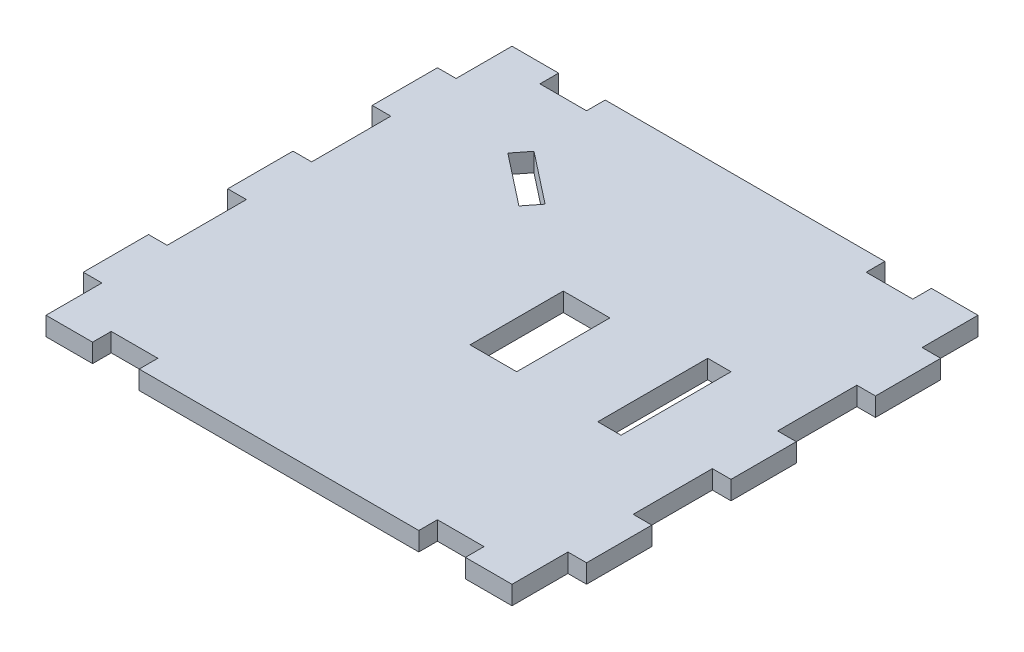
SolidWorks part; units mm, degrees
ref_plane "Front Plane" through (0, 0, 0) normal (0, 0, 1) x (1, 0, 0)
ref_plane "Top Plane" through (0, 0, 0) normal (0, 1, 0) x (1, 0, 0)
ref_plane "Right Plane" through (0, 0, 0) normal (1, 0, 0) x (0, 0, -1)
sketch "Sketch1" plane through (0, 0, 0) normal (0, 1, 0) x (1, 0, 0)
  line L1 (-25, 25) -> (25, 25)
  line L2 (-25, 25) -> (-25, -25)
  line L3 (-25, -25) -> (25, -25)
  line L4 (25, 25) -> (25, -25)
  line L5 (-25, 25) -> (25, -25) construction
  line L6 (-25, -25) -> (25, 25) construction
  line L7 (25, -19) -> (27, -19)
  line L8 (25, -19) -> (25, -12)
  line L9 (25, -12) -> (27, -12)
  line L10 (27, -19) -> (27, -12)
  line L11 (25, -3.5) -> (27, -3.5)
  line L12 (25, -3.5) -> (25, 3.5)
  line L13 (25, 3.5) -> (27, 3.5)
  line L14 (27, -3.5) -> (27, 3.5)
  line L15 (25, 12) -> (27, 12)
  line L16 (25, 12) -> (25, 19)
  line L17 (25, 19) -> (27, 19)
  line L18 (27, 12) -> (27, 19)
  line L19 (14.5, 6.5) -> (17, 6.5)
  line L20 (14.5, 6.5) -> (14.5, -5.3)
  line L21 (14.5, -5.3) -> (17, -5.3)
  line L22 (17, 6.5) -> (17, -5.3)
  line L23 (-25, 19) -> (-27, 19)
  line L24 (-25, 19) -> (-25, 12)
  line L25 (-25, 12) -> (-27, 12)
  line L26 (-27, 19) -> (-27, 12)
  line L27 (-25, 3.5) -> (-27, 3.5)
  line L28 (-25, 3.5) -> (-25, -3.5)
  line L29 (-25, -3.5) -> (-27, -3.5)
  line L30 (-27, 3.5) -> (-27, -3.5)
  line L31 (-25, -12) -> (-27, -12)
  line L32 (-25, -12) -> (-25, -19)
  line L33 (-25, -19) -> (-27, -19)
  line L34 (-27, -12) -> (-27, -19)
  point P0 (0, 0)
  dimension "D1" = 50
  dimension "D2" = 50
  dimension "D3" = 2
  dimension "D4" = 2
  dimension "D5" = 2
  dimension "D6" = 7
  dimension "D7" = 7
  dimension "D8" = 7
  dimension "D9" = 6
  dimension "D10" = 8.5
  dimension "D11" = 8.5
  dimension "D12" = 6
  dimension "D13" = 2.5
  dimension "D14" = 11.8
  dimension "D15" = 18.5
  dimension "D16" = 19.7
  dimension "D17" = 8
  dimension "D18" = 7
  dimension "D19" = 7
  dimension "D20" = 7
  dimension "D21" = 2
  dimension "D22" = 2
  dimension "D23" = 2
  dimension "D24" = 8.5
  dimension "D25" = 8.5
  dimension "D26" = 6
  dimension "D27" = 6
extrude "Boss-Extrude1" add sketch "Sketch1" along normal blind 2 contours L4 L1 L2 L3 L19 L22 L21 L20 | L11 L14 L13 L4 | L15 L18 L17 L4 | L7 L10 L9 L4 | L27 L30 L29 L2 | L31 L34 L33 L2 | L26 L25 L24 L23
sketch "Sketch3" plane through (0, 2, 0) normal (0, 1, 0) x (1, 0, 0)
  line L0 (-25, 25) -> (25, 25) construction
  line L1 (15, 25) -> (20, 25)
  line L2 (15, 25) -> (15, 23)
  line L3 (15, 23) -> (20, 23)
  line L4 (20, 25) -> (20, 23)
  line L5 (25, 25) -> (25, 19) construction
  line L6 (-25, -25) -> (25, -25) construction
  line L7 (15, -25) -> (20, -25)
  line L8 (15, -25) -> (15, -23)
  line L9 (15, -23) -> (20, -23)
  line L10 (20, -25) -> (20, -23)
  line L11 (25, -19) -> (25, -25) construction
  line L12 (-25, 25) -> (25, 25) construction
  line L13 (-15, 25) -> (-20, 25)
  line L14 (-15, 25) -> (-15, 23)
  line L15 (-15, 23) -> (-20, 23)
  line L16 (-20, 25) -> (-20, 23)
  line L17 (-25, -25) -> (25, -25) construction
  line L18 (-15, -25) -> (-20, -25)
  line L19 (-15, -25) -> (-15, -23)
  line L20 (-15, -23) -> (-20, -23)
  line L21 (-20, -25) -> (-20, -23)
  line L22 (-25, -19) -> (-25, -25) construction
  line L23 (-25, 25) -> (-25, 19) construction
  dimension "D1" = 5
  dimension "D2" = 2
  dimension "D3" = 5
  dimension "D4" = 2
  dimension "D5" = 5
  dimension "D6" = 5
  dimension "D7" = 5
  dimension "D8" = 5
  dimension "D9" = 2
  dimension "D10" = 2
  dimension "D11" = 5
  dimension "D12" = 5
extrude "Cut-Extrude1" cut sketch "Sketch3" against normal blind 2
sketch "Sketch4" plane through (0, 2, 0) normal (0, 1, 0) x (1, 0, 0)
  line L0 (-25, -25) -> (-20, -25) construction
  line L1 (5.5, 5) -> (0.5, 5)
  line L2 (5.5, 5) -> (5.5, -5)
  line L3 (5.5, -5) -> (0.5, -5)
  line L4 (0.5, 5) -> (0.5, -5)
  line L5 (5.5, 5) -> (0.5, -5) construction
  line L6 (5.5, -5) -> (0.5, 5) construction
  line L7 (-25, 25) -> (-20, 25) construction
  line L9 (14.5, 6.5) -> (14.5, -5.3) construction
  point P0 (3, 0)
  dimension "D1" = 10
  dimension "D2" = 5
  dimension "D3" = 20
  dimension "D4" = 20
  dimension "D5" = 9
extrude "Cut-Extrude2" cut sketch "Sketch4" against normal blind 2
sketch "Sketch5" plane through (0, 2, 0) normal (0, 1, 0) x (1, 0, 0)
  line L0 (-25, 25) -> (0.5, 5) construction
  line L1 (-14.0568, 16.4171) -> (-8.5488, 12.0971)
  line L2 (-14.0568, 16.4171) -> (-15.2911, 14.8434)
  line L3 (-8.5488, 12.0971) -> (-9.7831, 10.5234)
  line L4 (-15.2911, 14.8434) -> (-9.7831, 10.5234)
  dimension "D1" = 2
  dimension "D2" = 7
  dimension "D3" = 11.5
  dimension "D4" = 13.9076
extrude "Cut-Extrude3" cut sketch "Sketch5" against normal blind 2
